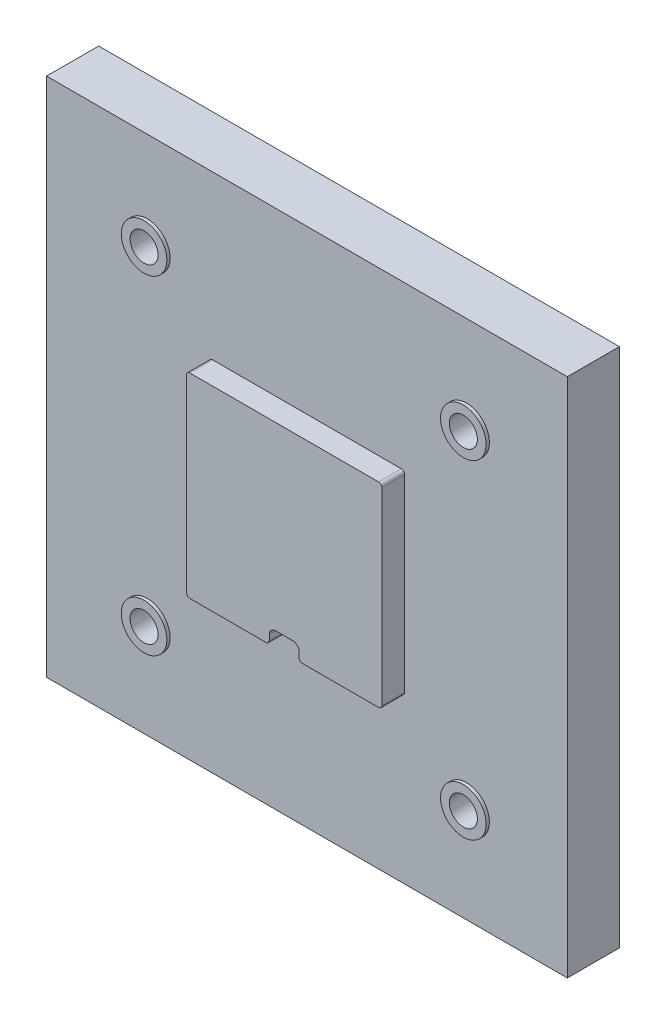
SolidWorks part; units mm, degrees
material "Copper"
ref_plane "Front Plane" through (0, 0, 0) normal (0, 0, 1) x (1, 0, 0)
ref_plane "Top Plane" through (0, 0, 0) normal (0, 1, 0) x (1, 0, 0)
ref_plane "Right Plane" through (0, 0, 0) normal (1, 0, 0) x (0, 0, -1)
ref_plane "Plane1"
sketch "Sketch1" plane through (0, 0, 0) normal (0, 0, 1) x (1, 0, 0)
  line L0 (-15, 15) -> (15, 15)
  line L1 (15, 15) -> (15, -15)
  line L2 (15, -15) -> (-15, -15)
  line L3 (-15, -15) -> (-15, 15)
  dimension "D1" = 30
  dimension "D2" = 30
extrude "Extrusion1" add sketch "Sketch1" along normal blind 3.5
sketch "Sketch2" plane through (0, 0, 0) normal (0, 0, -1) x (-1, 0, 0)
  line L0 (40, 40) -> (-40, 40)
  line L1 (-40, 40) -> (-40, -40)
  line L2 (-40, -40) -> (40, -40)
  line L3 (40, -40) -> (40, 40)
  line L4 (-15, 15) -> (15, 15) construction
  dimension "D1" = 80
  dimension "D2" = 80
  dimension "D3" = 25
  dimension "D4" = 30
extrude "Extrusion2" add sketch "Sketch2" along normal blind 8
sketch "Sketch3" plane through (0, 0, 3.5) normal (0, 0, 1) x (1, 0, 0)
  line L0 (-2.2929, -15) -> (2.2929, -15)
  line L1 (2.2929, -15) -> (2.2929, -13.7071)
  line L2 (1.2929, -12.7071) -> (-1.2929, -12.7071)
  line L3 (-2.2929, -13.7071) -> (-2.2929, -15)
  arc A0 (2.2929, -13.7071) -> (1.2929, -12.7071) centre (1.2929, -13.7071) ccw
  arc A1 (-1.2929, -12.7071) -> (-2.2929, -13.7071) centre (-1.2929, -13.7071) ccw
  dimension "D2" = 1
  dimension "D1" = 30
extrude "Extrusion3" cut sketch "Sketch3" against normal up to surface (3.5 mm away) up to face at (0, 0, 0)
fillet "Fillet1" radius 0.5 6 edges at (-15, 15, 1.75) (-15, -15, 1.75) (15, 15, 1.75) (15, -15, 1.75) (2.2929, -15, 1.75) (-2.2929, -15, 1.75)
hole_wizard "Hole2" positions "Sketch5" profile "Sketch4" legacy
sketch "Sketch5" plane through (0, 0, -8) normal (0, 0, -1) x (-1, 0, 0)
  point P1 (24.525, -25.25)
  point P2 (24.525, 25.25)
  point P3 (-24.525, 25.25)
  point P4 (-24.525, -25.25)
sketch "Sketch4" plane through (-24.525, -25.25, -8) normal (1, 0, 0) x (0, 1, 0)
  line L0 (0, 0) -> (0, 9.2934)
  line L1 (0, 9.2934) -> (2.1525, 8)
  line L2 (2.1525, 8) -> (2.1525, 4)
  line L3 (2.1525, 4) -> (3.5725, 4)
  line L4 (3.5725, 0) -> (0, 0)
  line L5 (0, -11.3109) -> (0, 121.1557) construction
  line L6 (0, 9.2934) -> (-2.1525, 8) construction
  line L7 (3.5725, 4) -> (3.5725, 0)
  dimension "Depth" = 8
  dimension "Drill Angle" = 118
  dimension "Diameter" = 4.305
  dimension "C-Bore Diameter" = 7.145
  dimension "C-Bore Depth" = 4
ref_plane "Plane2"
sketch "Sketch6" plane through (0, 0, 0) normal (0, 0, 1) x (1, 0, 0)
  circle A0 centre (-24.525, 25.25) radius 3.5
  circle A1 centre (24.525, 25.25) radius 3.5
  circle A2 centre (-24.525, -25.25) radius 3.5
  circle A3 centre (24.525, -25.25) radius 3.5
  circle A4 centre (-24.525, 25.25) radius 2.1525
  circle A5 centre (24.525, 25.25) radius 2.1525
  circle A6 centre (-24.525, -25.25) radius 2.1525
  circle A7 centre (24.525, -25.25) radius 2.1525
  dimension "D1" = 7
  dimension "D2" = 7
  dimension "D3" = 7
  dimension "D4" = 7
extrude "Extrusion4" add sketch "Sketch6" along normal blind 0.5 contours A0 A4 | A1 A5 | A2 A6 | A3 A7
